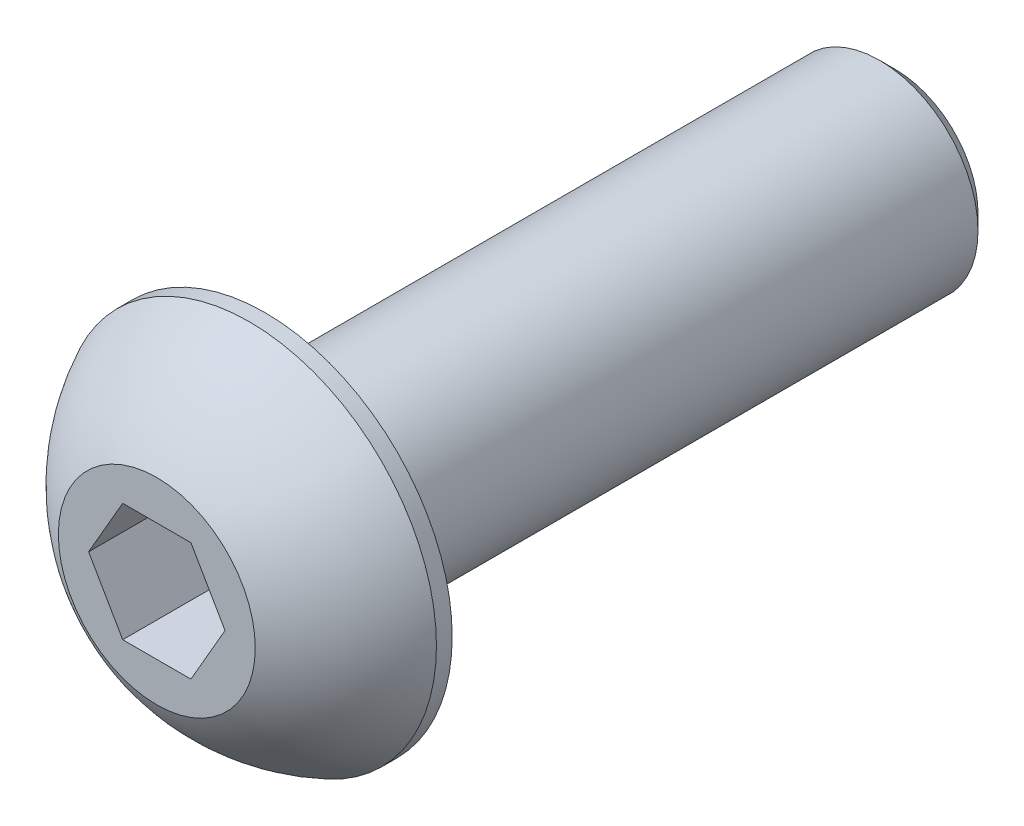
SolidWorks part; units mm, degrees
material "STAINLESS STEEL, 304"
ref_plane "Front Plane" through (0, 0, 0) normal (0, 0, 1) x (1, 0, 0)
ref_plane "Top Plane" through (0, 0, 0) normal (0, 1, 0) x (1, 0, 0)
ref_plane "Right Plane" through (0, 0, 0) normal (1, 0, 0) x (0, 0, -1)
other "Configuration Table"
sketch "Sketch1" plane through (0, 0, 0) normal (1, 0, 0) x (0, 0, -1)
  line L0 (-0.4, 4.75) -> (0, 4.75)
  line L1 (0, 4.75) -> (0, 2.5)
  line L2 (0, 2.5) -> (16, 2.5)
  line L3 (16, 2.5) -> (16, 0)
  line L4 (16, 0) -> (-2.75, 0) construction
  line L5 (-2.75, 0) -> (-2.75, 2.5)
  line L6 (16, 0) -> (-2.75, 0)
  arc A0 (-0.4, 4.75) -> (-2.75, 2.5) centre (1.8957, 0) ccw
  dimension "SIZE" = 5
  dimension "D2" = 5
  dimension "A" = 9.5
  dimension "S" = 0.4
  dimension "H" = 2.75
  dimension "L" = 16
revolve "Revolve1" add sketch "Sketch1" angle 360 mid plane about L4
cosmetic thread "Cosmetic Thread1"
sketch "Sketch2" plane through (0, 0, 2.75) normal (0, 0, 1) x (1, 0, 0)
  line L1 (1.7321, 0) -> (0.866, 1.5)
  line L2 (0.866, 1.5) -> (-0.866, 1.5)
  line L3 (-0.866, 1.5) -> (-1.7321, 0)
  line L4 (-1.7321, 0) -> (-0.866, -1.5)
  line L5 (-0.866, -1.5) -> (0.866, -1.5)
  line L6 (0.866, -1.5) -> (1.7321, 0)
  circle A0 centre (0, 0) radius 1.5 construction
  dimension "J" = 3
extrude "Cut-Extrude1" cut sketch "Sketch2" against normal blind 4
chamfer "Chamfer1" distance 0.4 angle 45 1 edges at (0, 2.5, -16)
fillet "Fillet1" radius 0.2 1 edges at (0, 2.5, 0)
